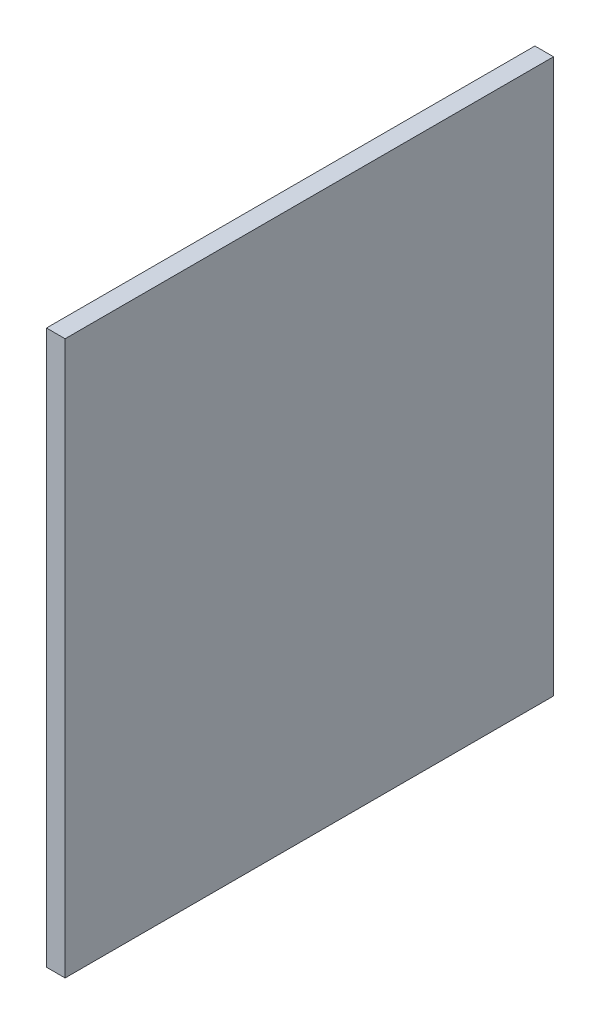
SolidWorks part; units mm, degrees
ref_plane "Front Plane" through (0, 0, 0) normal (0, 0, 1) x (1, 0, 0)
ref_plane "Top Plane" through (0, 0, 0) normal (0, 1, 0) x (1, 0, 0)
ref_plane "Right Plane" through (0, 0, 0) normal (1, 0, 0) x (0, 0, -1)
sketch "Sketch1" plane through (0, 0, 0) normal (1, 0, 0) x (0, 0, -1)
  line L1 (0, 0) -> (472, 0)
  line L2 (0, 0) -> (0, 535)
  line L3 (0, 535) -> (472, 535)
  line L4 (472, 0) -> (472, 535)
  dimension "D1" = 472
  dimension "D2" = 535
extrude "Boss-Extrude1" add sketch "Sketch1" along normal blind 18
